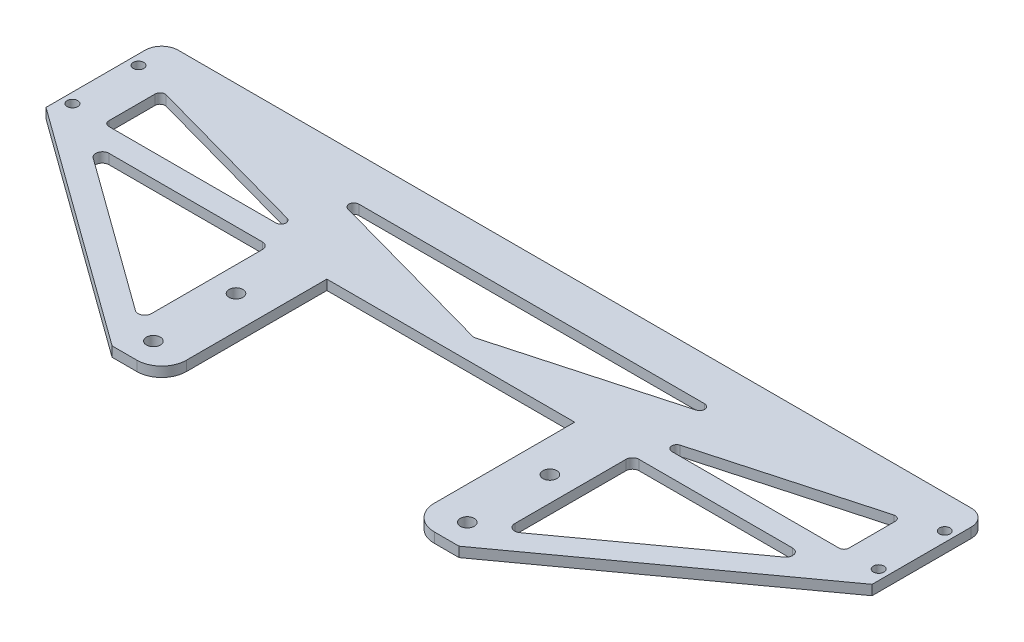
SolidWorks part; units mm, degrees
material "Thornel Mat VMA"
ref_plane "前视基准面" through (0, 0, 0) normal (0, 0, 1) x (1, 0, 0)
ref_plane "上视基准面" through (0, 0, 0) normal (0, 1, 0) x (1, 0, 0)
ref_plane "右视基准面" through (0, 0, 0) normal (1, 0, 0) x (0, 0, -1)
sketch "草图1" plane through (0, 0, 0) normal (0, 1, 0) x (1, 0, 0)
  line L0 (122, 0) -> (122, -25) construction
  line L1 (0, 0) -> (244, 0) construction
  line L2 (0, 0) -> (0, 20) construction
  line L3 (0, 20) -> (244, 20) construction
  line L4 (244, 0) -> (244, 20) construction
  line L5 (74.5, -25) -> (169.5, -25) construction
  line L6 (74.5, -25) -> (74.5, -50) construction
  line L7 (74.5, -50) -> (169.5, -50) construction
  line L8 (169.5, -25) -> (169.5, -50) construction
  line L9 (-3, 30) -> (-3, -5)
  line L10 (-3, -5) -> (69.5, -57.5)
  line L11 (69.5, -57.5) -> (84.5, -57.5)
  line L12 (-3, 30) -> (247, 30)
  line L13 (247, -5) -> (174.5, -57.5)
  line L14 (247, 30) -> (247, -5)
  line L15 (18.5593, -7.5) -> (65, -7.5)
  line L16 (67, -9.5) -> (67, -43.1295)
  line L17 (63.827, -44.7494) -> (17.3863, -11.1199)
  line L18 (84.5, -57.5) -> (84.5, -7.5)
  line L21 (180.173, -44.7494) -> (226.6137, -11.1199)
  line L22 (177, -9.5) -> (177, -43.1295)
  line L23 (225.4407, -7.5) -> (179, -7.5)
  line L24 (84.5, -7.5) -> (159.5, -7.5)
  line L25 (159.5, -7.5) -> (159.5, -57.5)
  line L26 (159.5, -57.5) -> (174.5, -57.5)
  circle A0 centre (0, 20) radius 1.6
  circle A1 centre (0, 0) radius 1.6
  circle A2 centre (244, 20) radius 1.6
  circle A3 centre (244, 0) radius 1.6
  circle A4 centre (74.5, -25) radius 2.1
  circle A5 centre (169.5, -25) radius 2.1
  circle A6 centre (74.5, -50) radius 2.1
  circle A7 centre (169.5, -50) radius 2.1
  arc A8 (67, -43.1295) -> (63.827, -44.7494) centre (65, -43.1295) cw
  arc A9 (65, -7.5) -> (67, -9.5) centre (65, -9.5) cw
  arc A10 (17.3863, -11.1199) -> (18.5593, -7.5) centre (18.5593, -9.5) cw
  arc A13 (177, -43.1295) -> (180.173, -44.7494) centre (179, -43.1295) ccw
  arc A14 (179, -7.5) -> (177, -9.5) centre (179, -9.5) ccw
  arc A15 (226.6137, -11.1199) -> (225.4407, -7.5) centre (225.4407, -9.5) ccw
  dimension "D3" = 3.2
  dimension "D4" = 25
  dimension "D7" = 4.2
  dimension "D16" = 2
  dimension "D17" = 10
  dimension "D1" = 20
  dimension "D2" = 244
  dimension "D5" = 95
  dimension "D6" = 25
  dimension "D8" = 3
  dimension "D9" = 10
  dimension "D10" = 5
  dimension "D11" = 7.5
  dimension "D12" = 5
  dimension "D13" = 7
  dimension "D14" = 7.5
  dimension "D15" = 7.5
  dimension "D18" = 10
extrude "凸台-拉伸1" add sketch "草图1" along normal blind 3
fillet "圆角1" radius 5 2 edges at (247, 1.5, -30) (-3, 1.5, -30)
fillet "圆角2" radius 7.5 2 edges at (159.5, 1.5, 57.5) (84.5, 1.5, 57.5)
sketch "草图3" plane through (0, 3, 0) normal (0, 1, 0) x (1, 0, 0)
  line L0 (10, 15.0276) -> (10, 1)
  line L1 (11.5, -0.5) -> (62.1041, -0.5)
  line L2 (62.5048, 2.4455) -> (11.9007, 16.4731)
  line L3 (69.6919, 17) -> (174.3081, 17)
  line L5 (121.5993, -0.4455) -> (69.2912, 14.0545)
  line L6 (122, -7.5) -> (122, 30) construction
  line L7 (84.5, -7.5) -> (159.5, -7.5) construction
  line L8 (242, 30) -> (2, 30) construction
  line L9 (232.5, -0.5) -> (181.8959, -0.5)
  line L10 (234, 15.0276) -> (234, 1)
  line L11 (181.4952, 2.4455) -> (232.0993, 16.4731)
  line L12 (122.4007, -0.4455) -> (174.7088, 14.0545)
  line L13 (65, -7.5) -> (18.5593, -7.5) construction
  arc A0 (232.5, -0.5) -> (234, 1) centre (232.5, 1) ccw
  arc A1 (234, 15.0276) -> (232.0993, 16.4731) centre (232.5, 15.0276) ccw
  arc A2 (181.8959, -0.5) -> (181.4952, 2.4455) centre (181.8959, 1) cw
  arc A3 (174.7088, 14.0545) -> (174.3081, 17) centre (174.3081, 15.5) ccw
  arc A4 (122.4007, -0.4455) -> (121.5993, -0.4455) centre (122, 1) cw
  arc A5 (69.6919, 17) -> (69.2912, 14.0545) centre (69.6919, 15.5) ccw
  arc A6 (62.1041, -0.5) -> (62.5048, 2.4455) centre (62.1041, 1) ccw
  arc A7 (10, 1) -> (11.5, -0.5) centre (11.5, 1) ccw
  arc A8 (10, 15.0276) -> (11.9007, 16.4731) centre (11.5, 15.0276) cw
  circle A9 centre (0, 20) radius 1.6 construction
  point P21 (234, -0.5)
  point P24 (234, 17)
  point P27 (170.8695, -0.5)
  point P30 (185.3346, 17)
  point P33 (122, -0.5566)
  point P36 (58.6654, 17)
  point P39 (73.1305, -0.5)
  point P42 (10, -0.5)
  point P45 (10, 17)
  dimension "D3" = 1.5
  dimension "D1" = 7
  dimension "D2" = 13
  dimension "D4" = 10
  dimension "D5" = 8.5
  dimension "D6" = 13
extrude "切除-拉伸1" cut sketch "草图3" against normal through all
